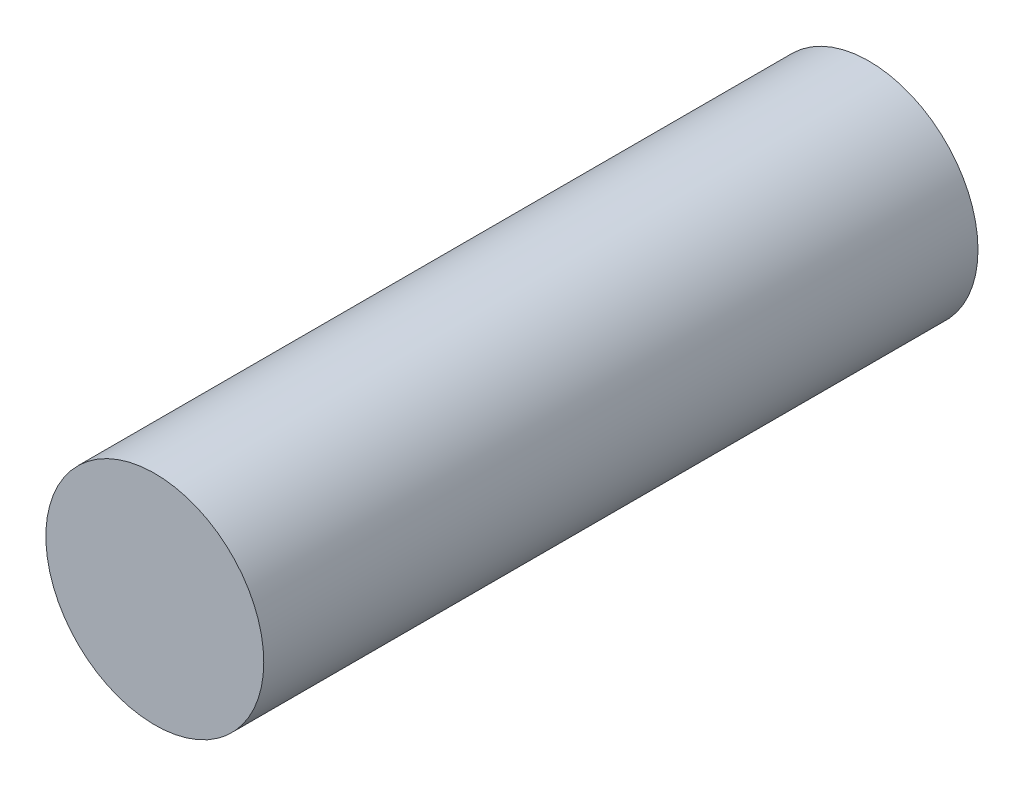
SolidWorks part; units mm, degrees
ref_plane "Front Plane" through (0, 0, 0) normal (0, 0, 1) x (1, 0, 0)
ref_plane "Top Plane" through (0, 0, 0) normal (0, 1, 0) x (1, 0, 0)
ref_plane "Right Plane" through (0, 0, 0) normal (1, 0, 0) x (0, 0, -1)
sketch "Sketch1" plane through (0, 0, 0) normal (0, 0, 1) x (1, 0, 0)
  circle A0 centre (0, 0) radius 50.8
  dimension "D1" = 101.6
extrude "Boss-Extrude1" add sketch "Sketch1" along normal blind 333
